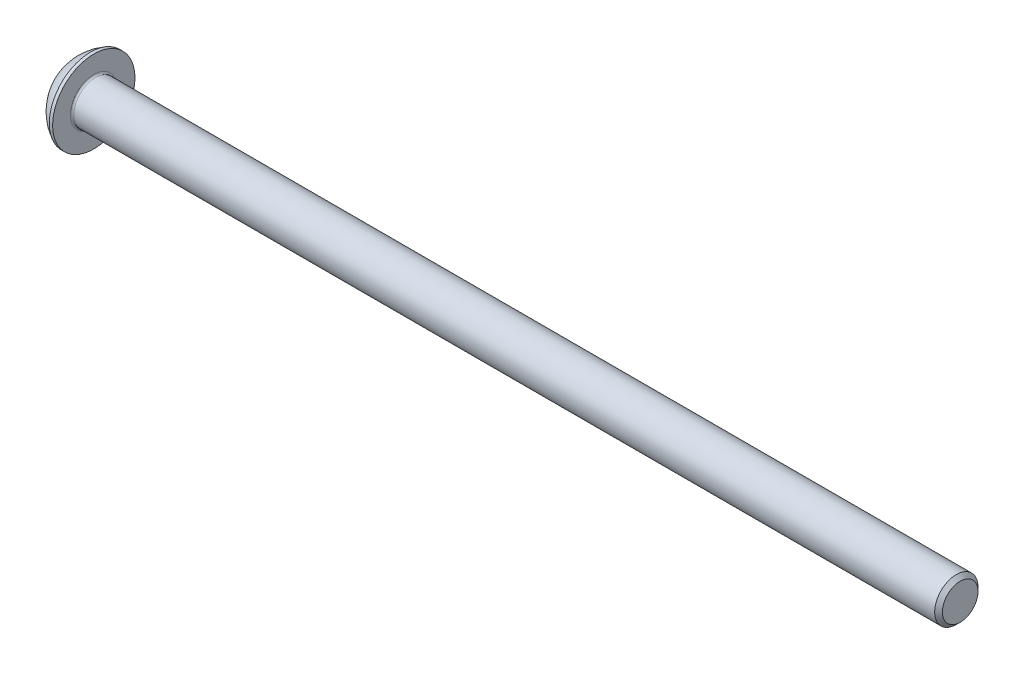
SolidWorks part; units mm, degrees
ref_plane "Plane1" through (0, 0, 0) normal (0, 0, 1) x (1, 0, 0)
ref_plane "Plane2" through (0, 0, 0) normal (0, 1, 0) x (1, 0, 0)
ref_plane "Plane3" through (0, 0, 0) normal (1, 0, 0) x (0, 0, -1)
other "Configuration Table"
sketch "BodySke" plane through (0, 0, 0) normal (0, 0, 1) x (1, 0, 0)
  line L0 (102.75, 0) -> (102.75, 2.055)
  line L1 (102.305, 2.5) -> (2.75, 2.5)
  line L2 (2.75, 2.5) -> (2.75, 4.75)
  line L3 (2.75, 4.75) -> (2.37, 4.75)
  line L4 (0, 0) -> (101.6, 0) construction
  line L5 (2.75, -4.75) -> (2.37, -4.75) construction
  line L6 (55.6768, -2.5) -> (2.75, -2.5) construction
  line L7 (102.75, 0) -> (0, 0)
  line L8 (0, 2.375) -> (0, -2.375) construction
  line L9 (0, 0) -> (0, 2.375)
  line L10 (102.75, 2.055) -> (102.305, 2.5)
  line L11 (102.75, -2.055) -> (102.305, -2.5) construction
  line L12 (3.55, 9.525) -> (3.55, -2.5) construction
  line L13 (92.75, 9.525) -> (92.75, -2.5) construction
  arc A1 (0, 2.375) -> (2.37, 4.75) centre (4.755, 0) cw
  dimension "Diameter" = 5
  dimension "Length" = 100
  dimension "Head_dia" = 9.5
  dimension "D1" = 4.75
  dimension "Head_ht" = 2.75
  dimension "Head_side_ht" = 0.38
  dimension "Minor_dia" = 4.11
  dimension "Body_ch_ang" = 45
  dimension "Advance" = 0.8
  dimension "Thread_nom" = 10
revolve "BaseBody" add sketch "BodySke" angle 360 about L4
cosmetic thread "ThreadCosmetic" [suppressed] parameters "Thread_length"=10, "Thread_minor"=4.11
fillet "Fillet1" radius 0.2 1 edges at (2.75, 0, 2.5)
sketch "Sketch2" plane through (0, 0, 0) normal (0, 0, 1) x (1, 0, 0)
  line L0 (0, 1.5) -> (1.56, 1.5)
  line L1 (1.56, 1.5) -> (2.426, 0)
  line L3 (2.426, 0) -> (0, 0)
  line L4 (0, 0) -> (0, 1.5)
  line L5 (0, -1.5) -> (1.56, -1.5) construction
  line L6 (0, 0) -> (47.625, 0) construction
  dimension "D2" = 60
  dimension "PreBroach_depth" = 1.56
  dimension "PreBroach_dia" = 3
revolve "PreBroach" cut sketch "Sketch2" angle 360 about L6
sketch "Sketch3" plane through (0, 0, 0) normal (1, 0, 0) x (0, 0, -1)
  line L0 (-1.5, -0.866) -> (-1.5, 0.866)
  line L1 (-1.5, 0.866) -> (0, 1.7321)
  line L2 (0, 1.7321) -> (1.5, 0.866)
  line L3 (1.5, 0.866) -> (1.5, -0.866)
  line L4 (1.5, -0.866) -> (0, -1.7321)
  line L5 (0, -1.7321) -> (-1.5, -0.866)
  dimension "Hex_size" = 3
  dimension "D3" = 3
  dimension "D1" = 1.5
  dimension "D2" = 1.5
extrude "Hex" cut sketch "Sketch3" along normal blind 1.56
sketch "ThdSchSke" plane through (0, 0, 0) normal (0, 0, 1) x (1, 0, 0)
  line L0 (92.75, -2.055) -> (92.4384, -2.5)
  line L1 (92.75, -2.055) -> (93.0616, -2.5)
  line L2 (93.0616, -2.5) -> (93.0616, -3.125)
  line L3 (-3.175, 0) -> (5.1513, 0) construction
  line L5 (93.0616, -3.125) -> (92.4384, -3.125)
  line L6 (92.4384, -3.125) -> (92.4384, -2.5)
  dimension "Diameter" = 5
  dimension "Thread_minor" = 4.11
  dimension "SideAngle" = 55
  dimension "VeeAngle" = 70
  dimension "Overcut" = 6.25
  dimension "Start" = 92.75
revolve "ThreadSchematic" [suppressed] cut sketch "ThdSchSke" angle 360 about L3
pattern_linear "ThdSchPat" [suppressed]
equation "\"D1@BodySke\" = \"Head_dia@BodySke\" * .5"
equation "\"Thread_minor@ThreadCosmetic\" = \"Minor_dia@BodySke\""
equation "\"D1@Sketch3\" = \"Hex_size@Sketch3\" / 2"
equation "\"D2@Sketch3\" = \"D1@Sketch3\""
equation "\"D3@Sketch3\" = \"Hex_size@Sketch3\""
equation "\"Thread_length@ThreadCosmetic\" = ((sgn( (\"Length@BodySke\" - \"Advance@BodySke\" * 2.0) - \"Thread_nom@BodySke\" )-1)*( (\"Length@BodySke\" - \"Advance@BodySke\" * 2.0) - \"Thread_nom@BodySke\" ))/-2+ \"Thread_nom@BodySke\""
equation "\"Thread_minor@ThdSchSke\" = \"Minor_dia@BodySke\""
equation "\"Diameter@ThdSchSke\" = \"Diameter@BodySke\""
equation "\"Overcut@ThdSchSke\" = \"Diameter@BodySke\" * 1.25"
equation "\"Start@ThdSchSke\" = \"Head_ht@BodySke\" + \"Length@BodySke\" - \"Thread_length@ThreadCosmetic\"  '---Non-countersunk---"
equation "\"Num_threads@ThdSchPat\" = int( \"Thread_length@ThreadCosmetic\" / \"Advance@BodySke\" + 0.999 )  + 1"
equation "\"Advance@ThdSchPat\" = \"Thread_length@ThreadCosmetic\" /  (\"Num_threads@ThdSchPat\" - 1) 'relax it"
equation "\"Num_threads@ThdSchPat\" = \"Num_threads@ThdSchPat\" - sgn( \"Num_threads@ThdSchPat\" - 1) '---chamfered tips only---"
